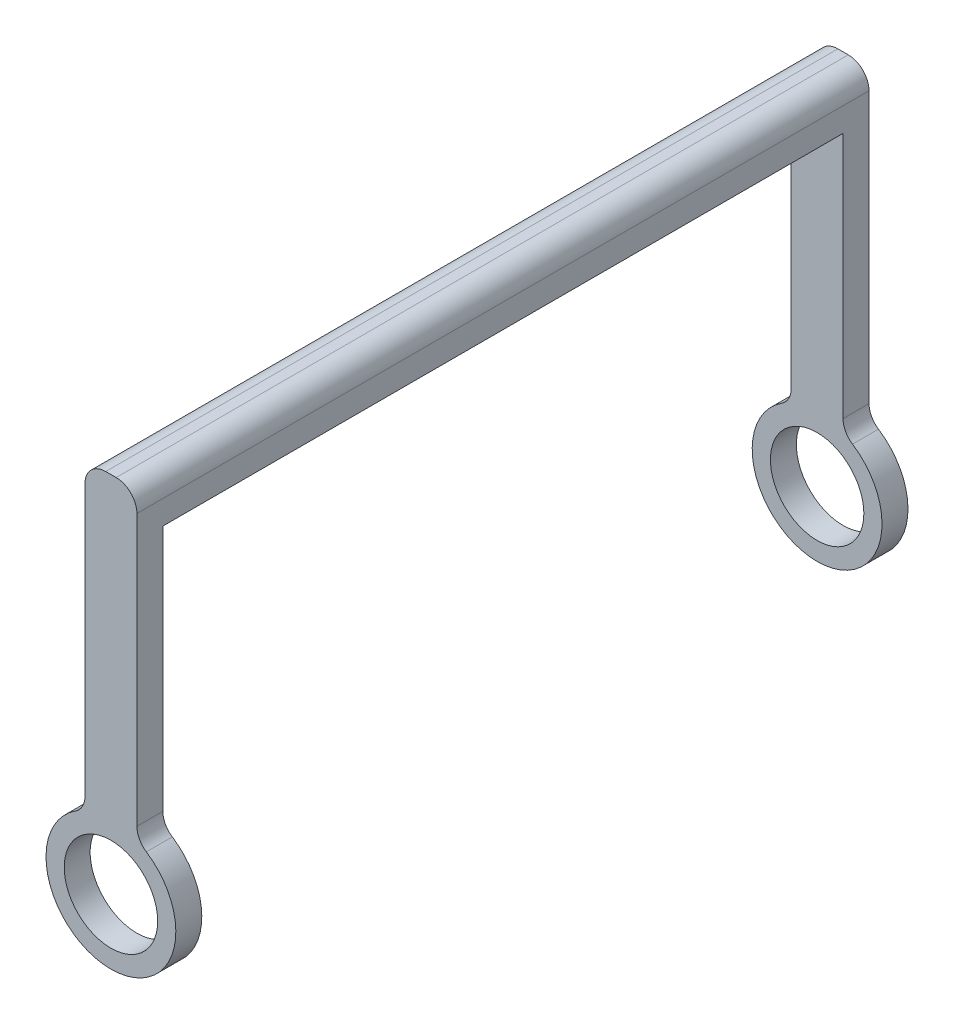
SolidWorks part; units mm, degrees
ref_plane "Front Plane" through (0, 0, 0) normal (0, 0, 1) x (1, 0, 0)
ref_plane "Top Plane" through (0, 0, 0) normal (0, 1, 0) x (1, 0, 0)
ref_plane "Right Plane" through (0, 0, 0) normal (1, 0, 0) x (0, 0, -1)
sketch "Sketch1" plane through (0, 0, 0) normal (0, 0, 1) x (1, 0, 0)
  line L0 (0, 0) -> (0, 79.1619) construction
  line L1 (-5, 13.8293) -> (-5, 66)
  line L2 (5, 13.8293) -> (5, 66)
  line L3 (-1, 70) -> (1, 70)
  circle A0 centre (0, 0) radius 9
  arc A1 (-6.8182, 10.4768) -> (6.8182, 10.4768) centre (0, 0) ccw
  arc A2 (5, 13.8293) -> (6.8182, 10.4768) centre (9, 13.8293) ccw
  arc A3 (-5, 13.8293) -> (-6.8182, 10.4768) centre (-9, 13.8293) cw
  arc A4 (5, 66) -> (1, 70) centre (1, 66) ccw
  arc A5 (-5, 66) -> (-1, 70) centre (-1, 66) cw
  point P10 (5, 11.4564)
  point P13 (-5, 11.4564)
  point P16 (5, 70)
  point P19 (-5, 70)
  dimension "D1" = 18
  dimension "D2" = 25
  dimension "D5" = 4
  dimension "D3" = 70
  dimension "D4" = 5
extrude "Boss-Extrude1" add sketch "Sketch1" along normal mid plane 5
sketch "Sketch2" plane through (0, 0, 2.5) normal (0, 0, 1) x (1, 0, 0)
  line L0 (-5, 61.4014) -> (5, 61.4014)
  line L3 (5, 13.8293) -> (5, 66)
  line L4 (1, 70) -> (-1, 70)
  line L5 (-5, 66) -> (-5, 13.8293)
  line L6 (5, 61.4014) -> (5, 66)
  line L7 (1, 70) -> (-1, 70)
  line L8 (-5, 66) -> (-5, 61.4014)
  arc A5 (5, 13.8293) -> (6.8182, 10.4768) centre (9, 13.8293) ccw
  arc A6 (5, 66) -> (1, 70) centre (1, 66) ccw
  arc A7 (-1, 70) -> (-5, 66) centre (-1, 66) ccw
  arc A8 (-6.8182, 10.4768) -> (-5, 13.8293) centre (-9, 13.8293) ccw
  arc A9 (-6.8182, 10.4768) -> (6.8182, 10.4768) centre (0, 0) ccw
  arc A10 (5, 13.8293) -> (6.8182, 10.4768) centre (9, 13.8293) ccw
  arc A11 (5, 66) -> (1, 70) centre (1, 66) ccw
  arc A12 (-1, 70) -> (-5, 66) centre (-1, 66) ccw
  arc A13 (-6.8182, 10.4768) -> (-5, 13.8293) centre (-9, 13.8293) ccw
  arc A14 (-6.8182, 10.4768) -> (6.8182, 10.4768) centre (0, 0) ccw
  line M10 (5, 13.8293) -> (5, 66)
  arc M11 (5, 66) -> (1, 70) centre (1, 66) ccw
  line M12 (1, 70) -> (-1, 70)
  arc M13 (-1, 70) -> (-5, 66) centre (-1, 66) ccw
  line M14 (-5, 66) -> (-5, 13.8293)
  dimension "D1" = 0
extrude "Boss-Extrude2" add sketch "Sketch2" along normal blind 131 contours L0 M14 M10 M11 M12 M13
ref_plane "Plane1" through (0, 0, 68) normal (0, 0, 1) x (1, 0, 0)
mirror "Mirror1" about plane through (0, 0, 68) normal (0, 0, 1) of "Boss-Extrude1"
